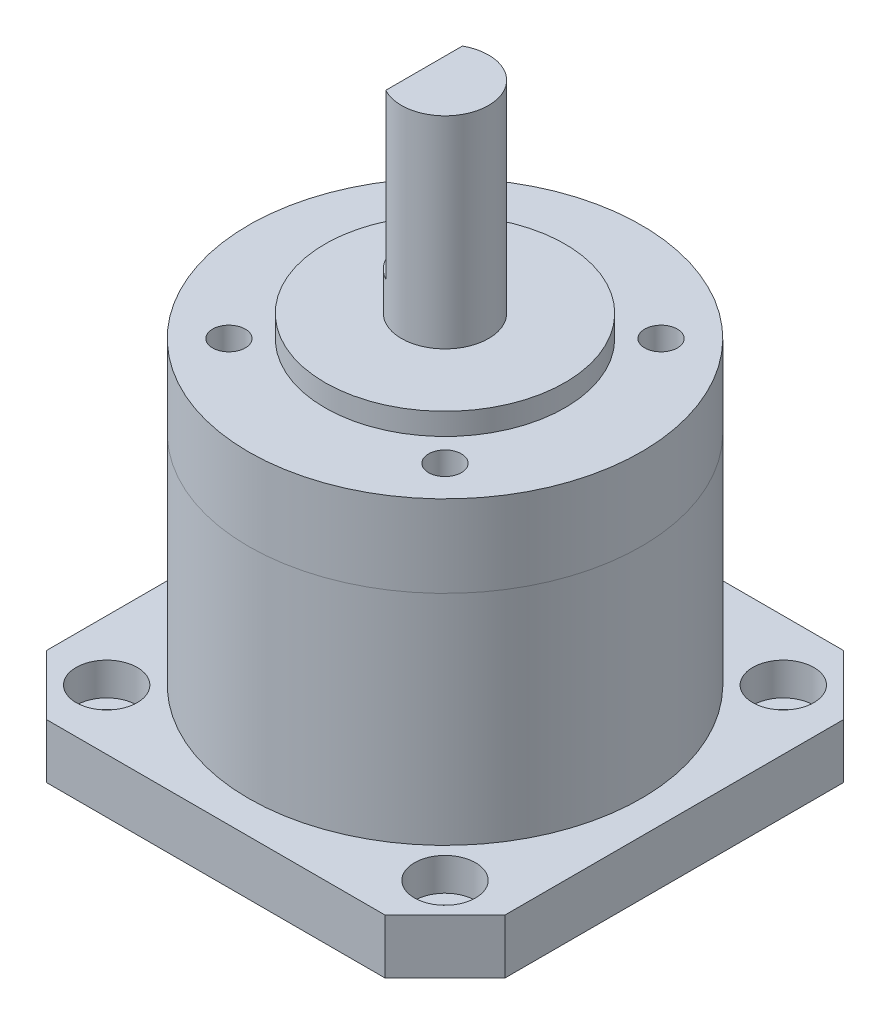
SolidWorks part; units mm, degrees
ref_plane "前视基准面" through (0, 0, 0) normal (0, 0, 1) x (1, 0, 0)
ref_plane "上视基准面" through (0, 0, 0) normal (0, 1, 0) x (1, 0, 0)
ref_plane "右视基准面" through (0, 0, 0) normal (1, 0, 0) x (0, 0, -1)
sketch "草图1" plane through (0, 0, 0) normal (0, 1, 0) x (1, 0, 0)
  line L1 (-21, 21) -> (21, 21)
  line L2 (-21, 21) -> (-21, -21)
  line L3 (-21, -21) -> (21, -21)
  line L4 (21, 21) -> (21, -21)
  line L5 (-21, 21) -> (21, -21) construction
  line L6 (-21, -21) -> (21, 21) construction
  point P0 (0, 0)
  dimension "D1" = 42
extrude "凸台-拉伸1" add sketch "草图1" along normal blind 5
chamfer "倒角1" distance 5.5 4 edges at (-21, 2.5, 21) (21, 2.5, 21) (21, 2.5, -21) (-21, 2.5, -21)
sketch "草图2" plane through (0, 0, 0) normal (0, -1, 0) x (1, 0, 0)
  line L0 (10.1924, 0) -> (-10.1924, 0) construction
  line L1 (0, 0) -> (0, 29.6141) construction
  line L2 (-3.6102, 3.6102) -> (-29.2181, 29.2181) construction
  line L3 (9.2594, 9.2594) -> (34.522, 34.522) construction
  circle A0 centre (-15.5, 15.5) radius 1.5
  circle A1 centre (15.5, 15.5) radius 1.5
  circle A2 centre (15.5, -15.5) radius 1.5
  circle A3 centre (-15.5, -15.5) radius 1.5
  point P2 (0, 0)
  point P13 (0, 0)
  point P22 (0, 0)
  dimension "D2" = 3
  dimension "D1" = 45
  dimension "D3" = 15.5
  dimension "D4" = 4
extrude "切除-拉伸1" cut sketch "草图2" against normal up to surface (5 mm away) up to face at (0, 5, 0)
sketch "草图3" plane through (0, 5, 0) normal (0, 1, 0) x (1, 0, 0)
  circle A0 centre (0, 0) radius 18
  dimension "D1" = 36
extrude "凸台-拉伸2" add sketch "草图3" along normal blind 27.5
sketch "草图4" plane through (0, 32.5, 0) normal (0, 1, 0) x (1, 0, 0)
  line L0 (0, 0) -> (31.2836, 0) construction
  line L1 (0, 0) -> (0, 33.2252) construction
  line L2 (0, 0) -> (-16.9551, 16.9551) construction
  circle A0 centre (-9.8995, 9.8995) radius 1.5
  circle A1 centre (0, 0) radius 14
  circle A2 centre (9.8995, 9.8995) radius 1.5
  circle A3 centre (9.8995, -9.8995) radius 1.5
  circle A4 centre (-9.8995, -9.8995) radius 1.5
  point P20 (0, 0)
  dimension "D2" = 3
  dimension "D3" = 28
  dimension "D1" = 45
  dimension "D4" = 4
extrude "切除-拉伸2" cut sketch "草图4" against normal blind 4 contours A0 | A2 | A3 | A4
sketch "草图6" plane through (0, 32.5, 0) normal (0, 1, 0) x (1, 0, 0)
  circle A0 centre (0, 0) radius 11
  dimension "D1" = 22
extrude "凸台-拉伸3" add sketch "草图6" along normal blind 2 contours A0
sketch "草图7" plane through (0, 34.5, 0) normal (0, 1, 0) x (1, 0, 0)
  circle A0 centre (0, 0) radius 4
  dimension "D1" = 8
extrude "凸台-拉伸4" add sketch "草图7" along normal blind 18.5
sketch "草图8" plane through (0, 0, 0) normal (0, -1, 0) x (1, 0, 0)
  circle A0 centre (0, 0) radius 11
  dimension "D1" = 22
extrude "切除-拉伸3" cut sketch "草图8" against normal blind 3
sketch "草图9" plane through (0, 3, 0) normal (0, -1, 0) x (1, 0, 0)
  circle A0 centre (0, 0) radius 8
  dimension "D1" = 16
extrude "切除-拉伸4" cut sketch "草图9" against normal blind 10
ref_plane "基准面1" through (0, 25, 0) normal (0, 1, 0) x (1, 0, 0)
split line "分割线1"
sketch "草图11" plane through (0, 53, 0) normal (0, 1, 0) x (1, 0, 0)
  line L0 (-1.9142, 3.5122) -> (-1.9142, -3.5122)
  circle A0 centre (0, 0) radius 4
  circle A2 centre (0, 0) radius 4
  circle A3 centre (0, 0) radius 4
  circle M3 centre (0, 0) radius 4
  dimension "D1" = 0
extrude "切除-拉伸5" cut sketch "草图11" against normal blind 15 contours L0 M3
sketch "草图12" plane through (0, 5, 0) normal (0, 1, 0) x (1, 0, 0)
  circle A0 centre (-15.5, 15.5) radius 2.8
  circle A1 centre (15.5, 15.5) radius 2.8
  circle A2 centre (-15.5, -15.5) radius 2.8
  circle A3 centre (15.5, -15.5) radius 2.8
  dimension "D1" = 5.6
extrude "切除-拉伸6" cut sketch "草图12" against normal blind 3
